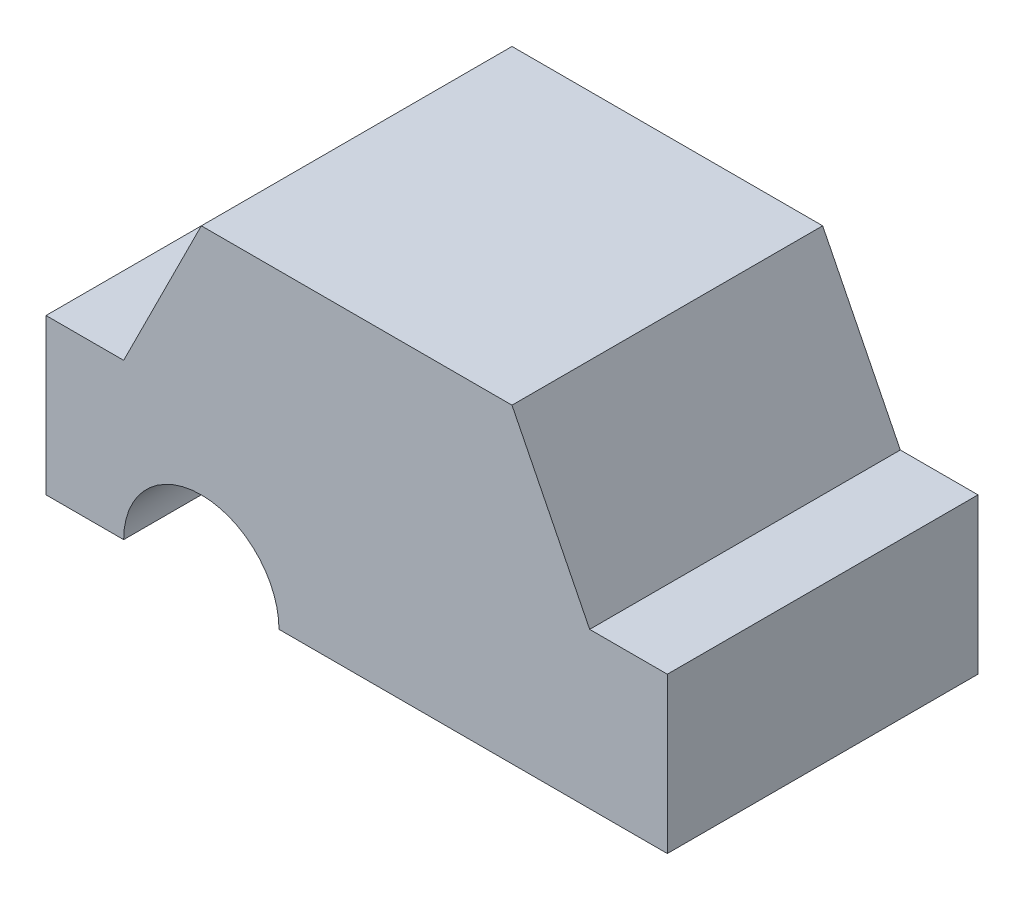
SolidWorks part; units mm, degrees
ref_plane "Front Plane" through (0, 0, 0) normal (0, 0, 1) x (1, 0, 0)
ref_plane "Top Plane" through (0, 0, 0) normal (0, 1, 0) x (1, 0, 0)
ref_plane "Right Plane" through (0, 0, 0) normal (1, 0, 0) x (0, 0, -1)
sketch "Sketch1" plane through (0, 0, 0) normal (0, 0, 1) x (1, 0, 0)
  line L0 (-111.0872, 18.2693) -> (-111.0872, -32.5307)
  line L1 (-34.8872, -32.5307) -> (15.9128, -32.5307)
  line L4 (92.1128, -32.5307) -> (92.1128, 18.2693)
  line L7 (-111.0872, -32.5307) -> (-85.6872, -32.5307)
  line L9 (92.1128, -32.5307) -> (66.7128, -32.5307)
  line L15 (-60.2872, 69.0693) -> (41.3128, 69.0693)
  line L17 (-85.6872, 18.2693) -> (-60.2872, 69.0693)
  line L18 (41.3128, 69.0693) -> (66.7128, 18.2693)
  line L19 (-111.0872, 18.2693) -> (-85.6872, 18.2693)
  line L20 (66.7128, 18.2693) -> (92.1128, 18.2693)
  line L21 (15.9128, -32.5307) -> (66.7128, -32.5307)
  arc A0 (-85.6872, -32.5307) -> (-60.2872, -7.1307) centre (-60.2872, -32.5307) cw
  arc A1 (-60.2872, -7.1307) -> (-34.8872, -32.5307) centre (-60.2872, -32.5307) cw
extrude "Boss-Extrude1" add sketch "Sketch1" along normal blind 101.6
